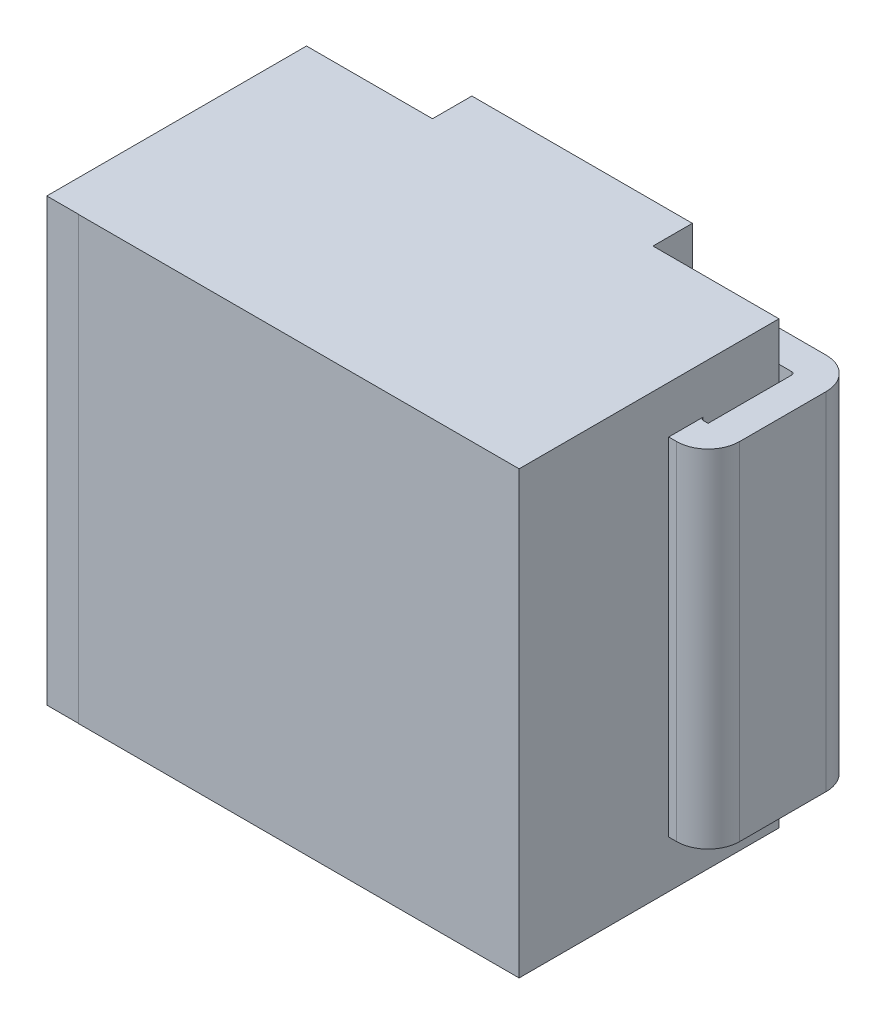
SolidWorks part; units mm, degrees
ref_plane "前视基准面" through (0, 0, 0) normal (0, 0, 1) x (1, 0, 0)
ref_plane "上视基准面" through (0, 0, 0) normal (0, 1, 0) x (1, 0, 0)
ref_plane "右视基准面" through (0, 0, 0) normal (1, 0, 0) x (0, 0, -1)
sketch "草图1" plane through (0, 0, 0) normal (0, 0, 1) x (1, 0, 0)
  line L1 (-22.0847, -9.9106) -> (-18.5847, -9.9106)
  line L2 (-22.0847, -9.9106) -> (-22.0847, -12.7106)
  line L3 (-22.0847, -12.7106) -> (-18.5847, -12.7106)
  line L4 (-18.5847, -9.9106) -> (-18.5847, -12.7106)
  dimension "D1" = 3.5
  dimension "D2" = 2.8
extrude "凸台-拉伸1" add sketch "草图1" along normal blind 1.9
sketch "草图3" plane through (0, -12.7106, 0) normal (0, -1, 0) x (1, 0, 0)
  line L0 (-22.0847, 0.95) -> (-18.5847, 0.95) construction
  line L1 (-22.0847, 1.9) -> (-22.0847, 0) construction
  line L2 (-18.5847, 1.9) -> (-18.5847, 0) construction
  line L3 (-20.3347, 0) -> (-20.3347, 1.9) construction
  line L4 (-22.0847, 0) -> (-18.5847, 0) construction
  line L5 (-22.0847, 1.9) -> (-18.5847, 1.9) construction
  line L6 (-21.8347, 1.9) -> (-21.8347, 0.95)
  line L7 (-18.5847, 1.9) -> (-18.8347, 1.9)
  line L8 (-21.8347, 0.95) -> (-22.0847, 0.95)
  line L9 (-22.0847, 0.95) -> (-22.0847, 1.9)
  line L10 (-22.0847, 1.9) -> (-21.8347, 1.9)
  line L11 (-18.8347, 1.9) -> (-18.8347, 0.95)
  line L12 (-18.8347, 0.95) -> (-18.5847, 0.95)
  line L13 (-18.5847, 0.95) -> (-18.5847, 1.9)
  line M3 (-18.5847, 1.9) -> (-22.0847, 1.9)
  line M4 (-22.0847, 1.9) -> (-22.0847, 0)
  line M6 (-18.5847, 0) -> (-18.5847, 1.9)
  dimension "D1" = 0.25
extrude "切除-拉伸2" cut sketch "草图3" against normal up to next contours L8 L6 M3 M4 | L11 L12 M6 M3
sketch "草图4" plane through (-22.0847, 0, 0) normal (-1, 0, 0) x (0, 0, 1)
  line L0 (0, -11.3106) -> (0.95, -11.3106) construction
  line L1 (0, -9.9106) -> (0, -12.7106) construction
  line L2 (0.95, -9.9106) -> (0.95, -12.7106) construction
  line L3 (0.95, -12.4106) -> (0, -12.4106)
  line L4 (0.95, -12.4106) -> (0.95, -12.7106)
  line L5 (0.95, -12.7106) -> (0, -12.7106)
  line L6 (0, -12.7106) -> (0, -12.4106)
  line L7 (0, -9.9106) -> (0, -10.2106)
  line L8 (0.95, -9.9106) -> (0, -9.9106)
  line L9 (0.95, -10.2106) -> (0.95, -9.9106)
  line L10 (0.95, -10.2106) -> (0, -10.2106)
  dimension "D1" = 2.2
extrude "切除-拉伸3" cut sketch "草图4" against normal blind 0.25
sketch "草图5" plane through (-18.5847, 0, 0) normal (1, 0, 0) x (0, 0, -1)
  line L0 (0, -11.3106) -> (-0.95, -11.3106) construction
  line L1 (0, -12.7106) -> (0, -9.9106) construction
  line L2 (-0.95, -9.9106) -> (-0.95, -12.7106) construction
  line L3 (-0.95, -10.2106) -> (0, -10.2106)
  line L4 (-0.95, -10.2106) -> (-0.95, -9.9106)
  line L5 (-0.95, -9.9106) -> (0, -9.9106)
  line L6 (0, -9.9106) -> (0, -10.2106)
  line L7 (0, -12.7106) -> (0, -12.4106)
  line L8 (-0.95, -12.7106) -> (0, -12.7106)
  line L9 (-0.95, -12.4106) -> (-0.95, -12.7106)
  line L10 (-0.95, -12.4106) -> (0, -12.4106)
  dimension "D1" = 2.2
extrude "切除-拉伸4" cut sketch "草图5" against normal blind 0.25
sketch "草图6" plane through (0, -12.7106, 0) normal (0, -1, 0) x (1, 0, 0)
  line L0 (-20.3347, 0) -> (-20.3347, 1.9) construction
  line L1 (-21.8347, 0) -> (-18.8347, 0) construction
  line L2 (-21.8347, 1.9) -> (-18.8347, 1.9) construction
  line L3 (-19.6347, 0.25) -> (-19.6347, 0)
  line L4 (-19.6347, 0.25) -> (-19.5847, 0.25)
  line L5 (-19.5847, 0.25) -> (-19.5847, 0)
  line L6 (-19.5847, 0) -> (-19.6347, 0)
  line L7 (-21.0847, 0) -> (-21.0347, 0)
  line L8 (-21.0847, 0.25) -> (-21.0847, 0)
  line L9 (-21.0347, 0.25) -> (-21.0847, 0.25)
  line L10 (-21.0347, 0.25) -> (-21.0347, 0)
  dimension "D1" = 1.4
  dimension "D2" = 0.05
  dimension "D3" = 0.25
extrude "切除-拉伸5" cut sketch "草图6" against normal through all
sketch "草图7" plane through (0, 0, 0) normal (0, 0, -1) x (-1, 0, 0)
  line L0 (19.5847, -12.4106) -> (18.8347, -12.4106)
  line L1 (19.5847, -12.7106) -> (19.5847, -12.4106)
  line L2 (19.5847, -9.9106) -> (19.5847, -12.7106) construction
  line L3 (19.5847, -12.7106) -> (18.8347, -12.7106)
  line L4 (18.8347, -12.7106) -> (18.8347, -12.4106)
  line L5 (20.3347, -12.7106) -> (20.3347, -9.9106) construction
  line L6 (21.0347, -12.7106) -> (19.6347, -12.7106) construction
  line L7 (19.6347, -9.9106) -> (21.0347, -9.9106) construction
  line L8 (22.0847, -11.3106) -> (18.5847, -11.3106) construction
  line L9 (22.0847, -10.2106) -> (22.0847, -12.4106) construction
  line L10 (18.5847, -12.4106) -> (18.5847, -10.2106) construction
  line L11 (21.0847, -12.7106) -> (21.8347, -12.7106)
  line L12 (21.8347, -12.7106) -> (21.8347, -12.4106)
  line L13 (21.0847, -12.7106) -> (21.0847, -12.4106)
  line L14 (21.0847, -12.4106) -> (21.8347, -12.4106)
  line L15 (19.5847, -9.9106) -> (18.8347, -9.9106)
  line L16 (18.8347, -9.9106) -> (18.8347, -10.2106)
  line L17 (19.5847, -10.2106) -> (18.8347, -10.2106)
  line L18 (19.5847, -9.9106) -> (19.5847, -10.2106)
  line L19 (21.0847, -9.9106) -> (21.8347, -9.9106)
  line L20 (21.0847, -9.9106) -> (21.0847, -10.2106)
  line L21 (21.8347, -9.9106) -> (21.8347, -10.2106)
  line L22 (21.0847, -10.2106) -> (21.8347, -10.2106)
extrude "切除-拉伸6" cut sketch "草图7" against normal blind 0.25
fillet "圆角1" radius 0.2 4 edges at (-22.0847, -11.3106, 0) (-18.5847, -11.3106, 0) (-18.5847, -11.3106, 0.95) (-22.0847, -11.3106, 0.95)
sketch "草图8" plane through (0, -12.7106, 0) normal (0, -1, 0) x (1, 0, 0)
  line L0 (-21.0847, 0.2) -> (-21.8847, 0.2)
  line L1 (-21.0847, 0.25) -> (-21.0847, 0) construction
  line L2 (-21.8847, 0.2) -> (-21.8847, 0.75)
  line L3 (-21.8847, 0.75) -> (-21.8347, 0.75)
  line L4 (-21.8347, 0.95) -> (-21.8347, 0.25) construction
  line L5 (-21.8347, 0.95) -> (-21.8847, 0.95) construction
  line L6 (-22.0847, 0.75) -> (-22.0847, 0.2) construction
  line L7 (-21.0847, 0) -> (-21.8847, 0) construction
  line L9 (-21.8347, 0.75) -> (-21.8347, 0.25)
  line L10 (-21.8347, 0.25) -> (-21.0847, 0.25)
  line L11 (-21.0847, 0.25) -> (-21.0847, 0.2)
  line L12 (-20.3347, 1.9) -> (-20.3347, 0) construction
  line L13 (-21.8347, 1.9) -> (-18.8347, 1.9) construction
  line L14 (-21.0347, 0) -> (-19.6347, 0) construction
  line L15 (-19.5847, 0.25) -> (-19.5847, 0.2)
  line L16 (-18.8347, 0.25) -> (-19.5847, 0.25)
  line L17 (-19.5847, 0.2) -> (-18.7847, 0.2)
  line L18 (-18.7847, 0.75) -> (-18.8347, 0.75)
  line L19 (-18.8347, 0.75) -> (-18.8347, 0.25)
  line L20 (-18.7847, 0.2) -> (-18.7847, 0.75)
  point P4 (-21.8597, 0.95)
  dimension "D1" = 0.2
  dimension "D2" = 0.2
  dimension "D3" = 0.2
extrude "切除-拉伸7" cut sketch "草图8" against normal through all
fillet "圆角2" radius 0.02 4 edges at (-18.7847, -11.3106, 0.2) (-21.8847, -11.3106, 0.2) (-21.8847, -11.3106, 0.75) (-18.8347, -11.3106, 0.75)
sketch "草图9" plane through (0, 0, 1.9) normal (0, 0, 1) x (1, 0, 0)
  line L0 (-21.8347, -12.7106) -> (-18.8347, -12.7106) construction
  line L1 (-21.6312, -12.7106) -> (-21.8347, -12.7106)
  line L2 (-21.6312, -12.7106) -> (-21.6312, -9.9106)
  line L3 (-21.6312, -9.9106) -> (-21.8347, -9.9106)
  line L4 (-21.8347, -12.7106) -> (-21.8347, -9.9106)
  line L5 (-21.8347, -9.9106) -> (-21.8347, -12.7106) construction
extrude "切除-拉伸8" cut sketch "草图9" against normal blind 0.001
